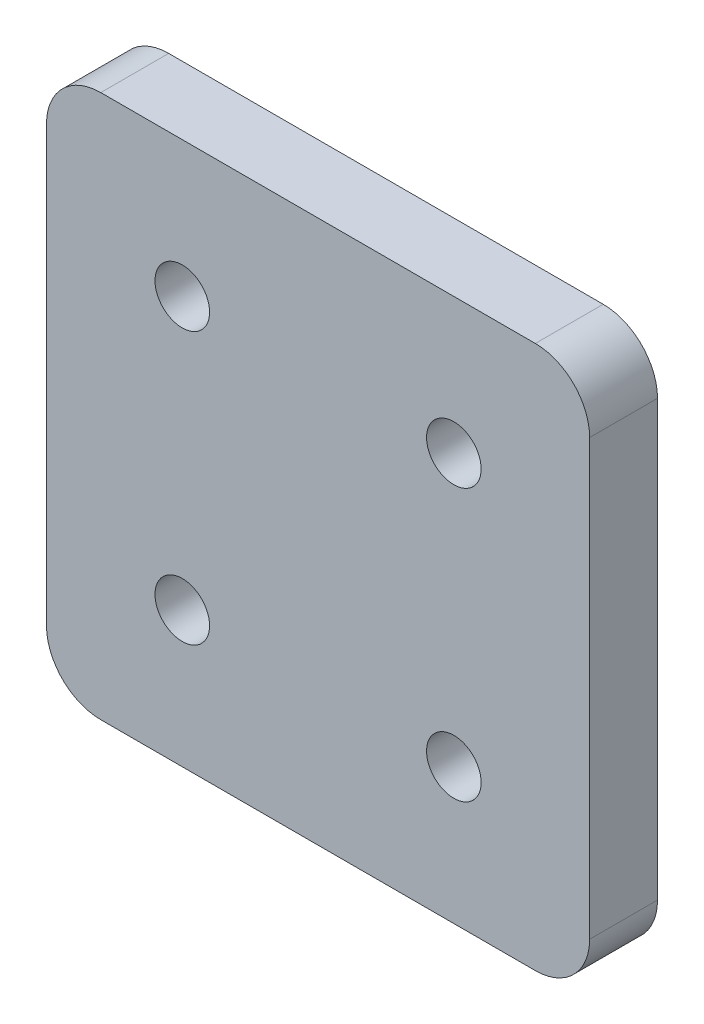
SolidWorks part; units mm, degrees
ref_plane "Front Plane" through (0, 0, 0) normal (0, 0, 1) x (1, 0, 0)
ref_plane "Top Plane" through (0, 0, 0) normal (0, 1, 0) x (1, 0, 0)
ref_plane "Right Plane" through (0, 0, 0) normal (1, 0, 0) x (0, 0, -1)
sketch "Sketch1" plane through (0, 0, 0) normal (0, 0, 1) x (1, 0, 0)
  line L0 (1.4879, 1.4879) -> (41.3092, 41.3092)
  line L1 (48.4934, 41.3092) -> (66.0947, 23.7079)
  line L2 (66.0947, 16.5237) -> (0.2589, -49.3121)
  line L3 (-3.3332, -50.8) -> (-58.42, -50.8)
  line L4 (-63.5, -45.72) -> (-63.5, -5.08)
  line L5 (-58.42, 0) -> (-2.1042, 0)
  arc A0 (66.0947, 23.7079) -> (66.0947, 16.5237) centre (62.5026, 20.1158) cw
  arc A1 (41.3092, 41.3092) -> (48.4934, 41.3092) centre (44.9013, 37.7171) cw
  arc A2 (-63.5, -5.08) -> (-58.42, 0) centre (-58.42, -5.08) cw
  arc A3 (-58.42, -50.8) -> (-63.5, -45.72) centre (-58.42, -45.72) cw
  arc A4 (0.2589, -49.3121) -> (-3.3332, -50.8) centre (-3.3332, -45.72) cw
  arc A5 (1.4879, 1.4879) -> (-2.1042, 0) centre (-2.1042, 5.08) cw
  circle A6 centre (-50.8, -12.7) radius 2.5527
  circle A7 centre (-25.4, -12.7) radius 2.5527
  circle A8 centre (-25.4, -38.1) radius 2.5527
  circle A9 centre (-50.8, -38.1) radius 2.5527
  point P11 (69.6868, 20.1158)
  point P14 (44.9013, 44.9013)
  point P17 (-63.5, 0)
  point P20 (-63.5, -50.8)
  point P25 (0, 0)
  dimension "D6" = 5.08
  dimension "D9" = 5.1054
  dimension "D10" = 25.4
  dimension "D11" = 25.4
  dimension "D12" = 12.7
  dimension "D13" = 12.7
  dimension "D1" = 45
  dimension "D2" = 50.8
  dimension "D3" = 35.052
  dimension "D4" = 63.5
  dimension "D5" = 63.5
  dimension "D7" = 2
  dimension "D8" = 2
extrude "Boss-Extrude1" add sketch "Sketch1" along normal blind 6.35
sketch "Sketch2" plane through (0, 0, 6.35) normal (0, 0, 1) x (1, 0, 0)
  line L0 (-2.1042, 0) -> (-58.42, 0) construction
  line L1 (-63.5, 0) -> (-17.78, 0)
  line L2 (-63.5, 0) -> (-63.5, -50.8)
  line L3 (-63.5, -50.8) -> (-17.78, -50.8)
  line L4 (-12.7, -5.08) -> (-12.7, -45.72)
  line L5 (-63.5, -5.08) -> (-63.5, -45.72) construction
  line L6 (-58.42, -50.8) -> (-3.3332, -50.8) construction
  line L13 (66.0947, 23.7079) -> (48.4934, 41.3092)
  line L14 (41.3092, 41.3092) -> (1.4879, 1.4879)
  line L15 (-2.1042, 0) -> (-58.42, 0)
  line L16 (-63.5, -5.08) -> (-63.5, -45.72)
  line L17 (-58.42, -50.8) -> (-3.3332, -50.8)
  line L18 (0.2589, -49.3121) -> (66.0947, 16.5237)
  line L19 (66.0947, 23.7079) -> (48.4934, 41.3092)
  line L20 (41.3092, 41.3092) -> (1.4879, 1.4879)
  line L21 (-2.1042, 0) -> (-58.42, 0)
  line L22 (-63.5, -5.08) -> (-63.5, -45.72)
  line L23 (-58.42, -50.8) -> (-3.3332, -50.8)
  line L24 (0.2589, -49.3121) -> (66.0947, 16.5237)
  circle A0 centre (-25.4, -12.7) radius 2.5527 construction
  arc A1 (-17.78, -50.8) -> (-12.7, -45.72) centre (-17.78, -45.72) ccw
  arc A2 (-17.78, 0) -> (-12.7, -5.08) centre (-17.78, -5.08) cw
  arc A4 (-63.5, -45.72) -> (-58.42, -50.8) centre (-58.42, -45.72) ccw construction
  arc A11 (66.0947, 16.5237) -> (66.0947, 23.7079) centre (62.5026, 20.1158) ccw
  arc A12 (48.4934, 41.3092) -> (41.3092, 41.3092) centre (44.9013, 37.7171) ccw
  arc A13 (-2.1042, 0) -> (1.4879, 1.4879) centre (-2.1042, 5.08) ccw
  arc A14 (-58.42, 0) -> (-63.5, -5.08) centre (-58.42, -5.08) ccw
  arc A15 (-63.5, -45.72) -> (-58.42, -50.8) centre (-58.42, -45.72) ccw
  arc A16 (-3.3332, -50.8) -> (0.2589, -49.3121) centre (-3.3332, -45.72) ccw
  arc A17 (66.0947, 16.5237) -> (66.0947, 23.7079) centre (62.5026, 20.1158) ccw
  arc A18 (48.4934, 41.3092) -> (41.3092, 41.3092) centre (44.9013, 37.7171) ccw
  arc A19 (-2.1042, 0) -> (1.4879, 1.4879) centre (-2.1042, 5.08) ccw
  arc A20 (-58.42, 0) -> (-63.5, -5.08) centre (-58.42, -5.08) ccw
  arc A21 (-63.5, -45.72) -> (-58.42, -50.8) centre (-58.42, -45.72) ccw
  arc A22 (-3.3332, -50.8) -> (0.2589, -49.3121) centre (-3.3332, -45.72) ccw
  arc M17 (66.0947, 16.5237) -> (66.0947, 23.7079) centre (62.5026, 20.1158) ccw
  line M18 (66.0947, 23.7079) -> (48.4934, 41.3092)
  arc M19 (48.4934, 41.3092) -> (41.3092, 41.3092) centre (44.9013, 37.7171) ccw
  line M20 (41.3092, 41.3092) -> (1.4879, 1.4879)
  arc M21 (1.4879, 1.4879) -> (-2.1042, 0) centre (-2.1042, 5.08) cw
  line M22 (-2.1042, 0) -> (-58.42, 0)
  line M26 (-58.42, -50.8) -> (-3.3332, -50.8)
  arc M27 (-3.3332, -50.8) -> (0.2589, -49.3121) centre (-3.3332, -45.72) ccw
  line M28 (0.2589, -49.3121) -> (66.0947, 16.5237)
  dimension "D1" = 12.7
  dimension "D2" = 0
extrude "Cut-Extrude1" cut sketch "Sketch2" against normal through all contours A2 L4 A1 M22 M26 M27 M28 M17 M18 M19 M20 M21
